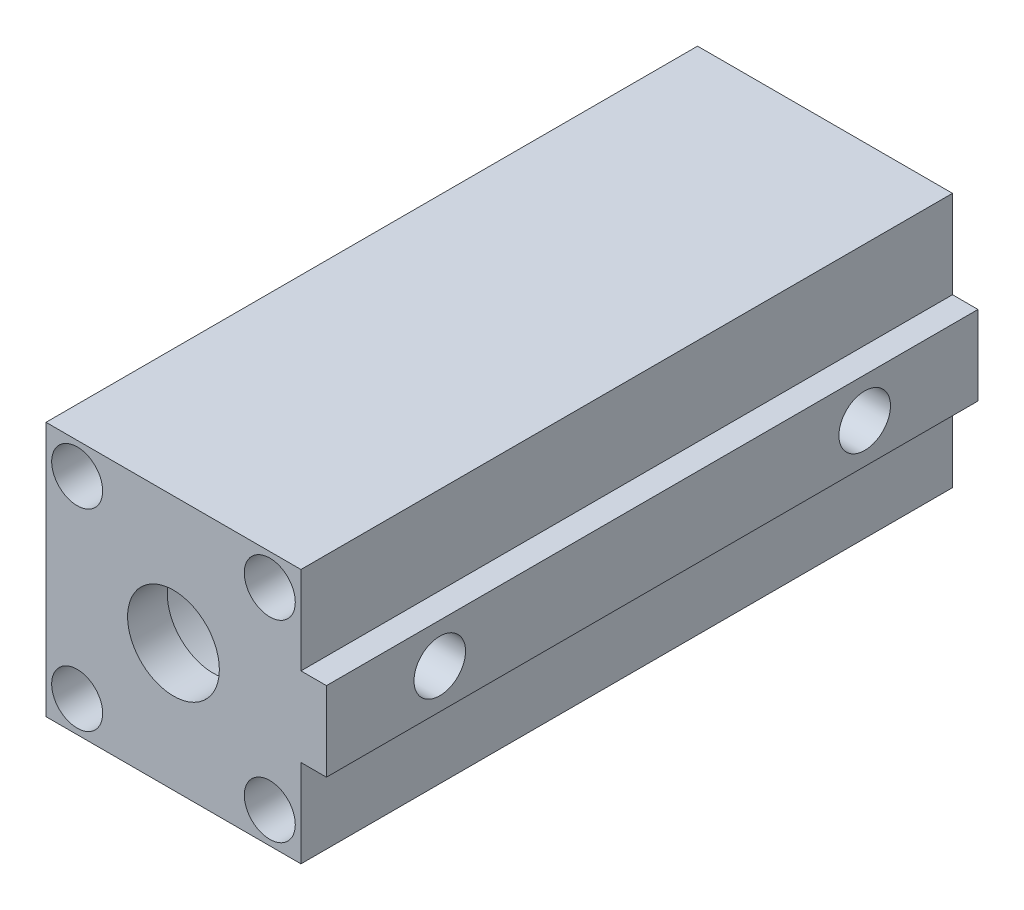
SolidWorks part; units mm, degrees
ref_plane "Front Plane" through (0, 0, 0) normal (0, 0, 1) x (1, 0, 0)
ref_plane "Top Plane" through (0, 0, 0) normal (0, 1, 0) x (1, 0, 0)
ref_plane "Right Plane" through (0, 0, 0) normal (1, 0, 0) x (0, 0, -1)
sketch "Sketch1" plane through (0, 0, 0) normal (0, 0, 1) x (1, 0, 0)
  line L0 (-22.5, -22.5) -> (22.5, -22.5)
  line L1 (22.5, -22.5) -> (22.5, 22.5)
  line L2 (22.5, 22.5) -> (-22.5, 22.5)
  line L3 (-22.5, 22.5) -> (-22.5, -22.5)
  circle A0 centre (-17, -17) radius 2.75
  circle A1 centre (-17, 17) radius 2.75
  circle A2 centre (17, -17) radius 2.75
  circle A3 centre (17, 17) radius 2.75
  circle A4 centre (0, 0) radius 16
extrude "SMC 45 mm square body and four 5.5 mm through holes" add sketch "Sketch1" along normal blind 115
sketch "Sketch2" plane through (0, 0, 0) normal (0, 0, 1) x (1, 0, 0)
  circle A0 centre (0, 0) radius 16
extrude "Head end clearance envelope" add sketch "Sketch2" along normal blind 7
sketch "Sketch3" plane through (0, 0, 0) normal (0, 0, 1) x (1, 0, 0)
  circle A0 centre (0, 0) radius 16
  circle A1 centre (0, 0) radius 8.1
extrude "Rod cover and 16 mm rod clearance" add sketch "Sketch3" along normal blind 7 from offset 108
sketch "Sketch4" plane through (0, 0, 0) normal (0, 0, 1) x (1, 0, 0)
  circle A0 centre (-17, -17) radius 4.5
  circle A1 centre (-17, 17) radius 4.5
  circle A2 centre (17, -17) radius 4.5
  circle A3 centre (17, 17) radius 4.5
extrude "Rear bolt head counterbores" cut sketch "Sketch4" along normal blind 7
sketch "Sketch5" plane through (0, 0, 0) normal (0, 0, 1) x (1, 0, 0)
  circle A0 centre (-17, -17) radius 4.5
  circle A1 centre (-17, 17) radius 4.5
  circle A2 centre (17, -17) radius 4.5
  circle A3 centre (17, 17) radius 4.5
extrude "Front mounting counterbores" cut sketch "Sketch5" along normal blind 7 from offset 108
sketch "Sketch6" plane through (0, 0, 0) normal (1, 0, 0) x (0, 0, -1)
  line L0 (-115, -7) -> (0, -7)
  line L1 (0, -7) -> (0, 7)
  line L2 (0, 7) -> (-115, 7)
  line L3 (-115, 7) -> (-115, -7)
extrude "Catalog 14 mm wide port boss projection" add sketch "Sketch6" along normal blind 4.6 from offset 22.4
sketch "Sketch7" plane through (0, 0, 0) normal (1, 0, 0) x (0, 0, -1)
  circle A0 centre (-20, 0) radius 4.55
  circle A1 centre (-95, 0) radius 4.55
extrude "Top Rc 1/8 ports, 20 mm from each end" cut sketch "Sketch7" against normal blind 7 from offset 27
